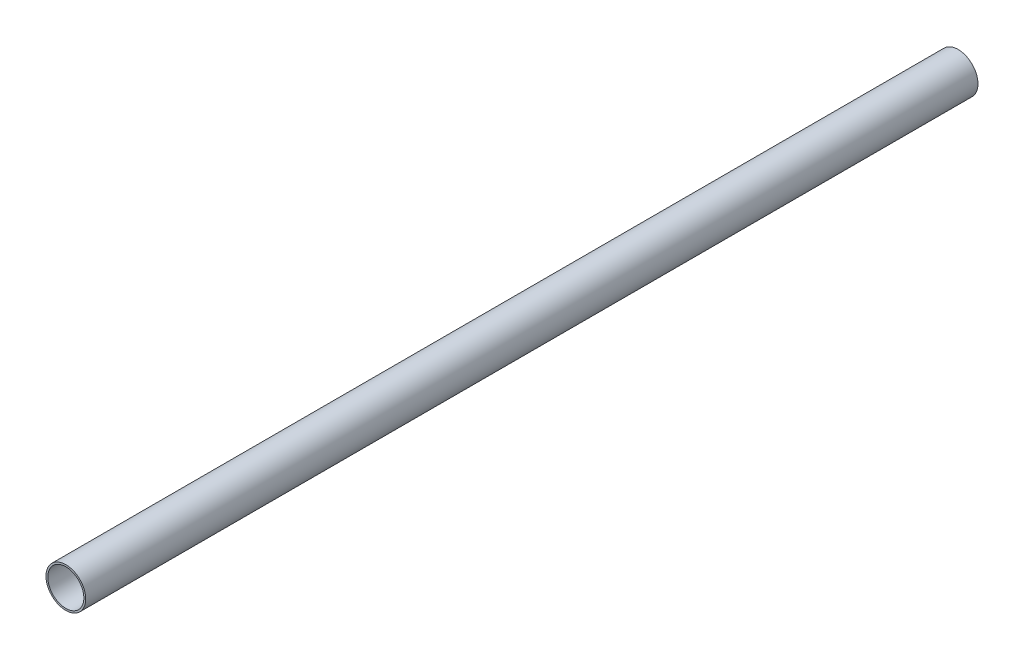
SolidWorks part; units mm, degrees
ref_plane "Front Plane" through (0, 0, 0) normal (0, 0, 1) x (1, 0, 0)
ref_plane "Top Plane" through (0, 0, 0) normal (0, 1, 0) x (1, 0, 0)
ref_plane "Right Plane" through (0, 0, 0) normal (1, 0, 0) x (0, 0, -1)
sketch "Sketch1" plane through (0, 0, 0) normal (0, 0, 1) x (1, 0, 0)
  circle A0 centre (2675.1058, 3025.346) radius 3.8862
  circle A1 centre (2675.1058, 3025.346) radius 3.5306
extrude "Boss-Extrude1" add sketch "Sketch1" along normal blind 174.625
